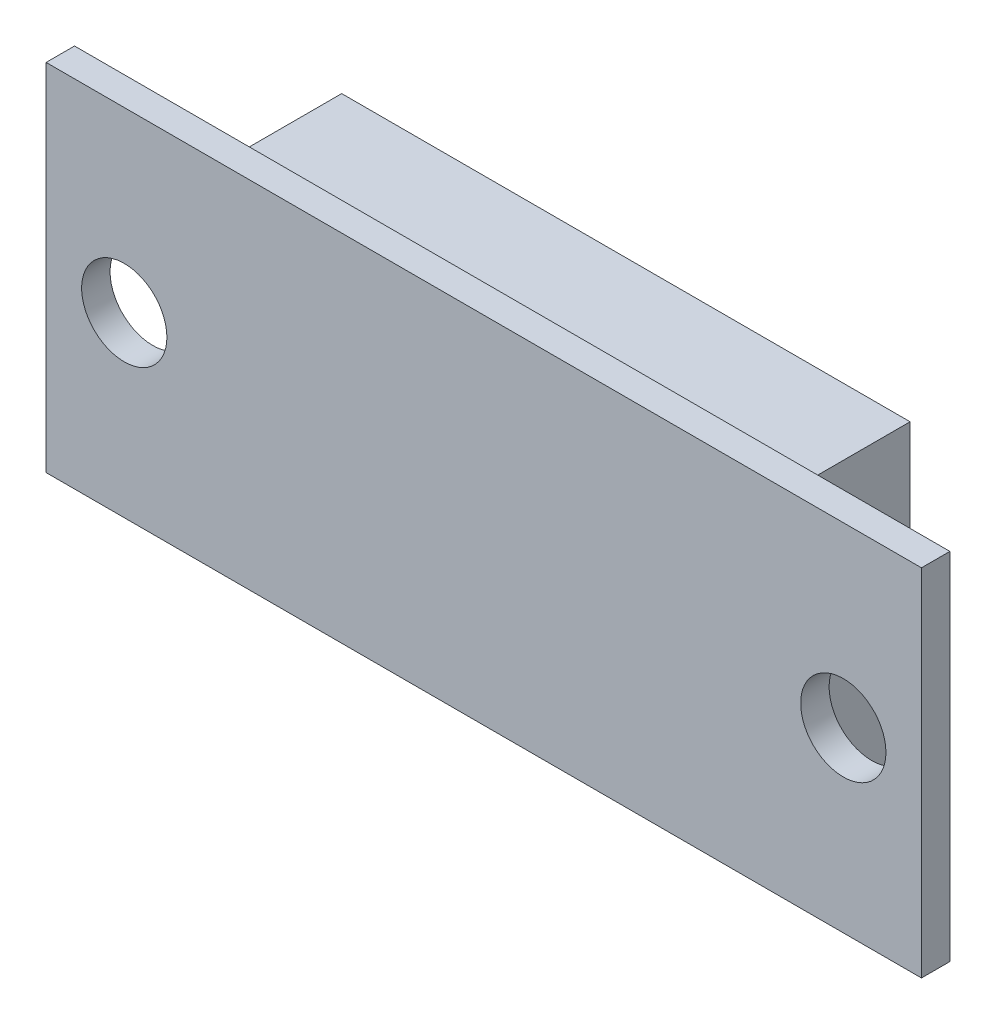
SolidWorks part; units mm, degrees
ref_plane "Front Plane" through (0, 0, 0) normal (0, 0, 1) x (1, 0, 0)
ref_plane "Top Plane" through (0, 0, 0) normal (0, 1, 0) x (1, 0, 0)
ref_plane "Right Plane" through (0, 0, 0) normal (1, 0, 0) x (0, 0, -1)
sketch "Sketch1" plane through (0, 0, 0) normal (0, 0, 1) x (1, 0, 0)
  line L1 (-10, 5.5) -> (10, 5.5)
  line L2 (-10, 5.5) -> (-10, -5.5)
  line L3 (-10, -5.5) -> (10, -5.5)
  line L4 (10, 5.5) -> (10, -5.5)
  line L5 (-10, 5.5) -> (10, -5.5) construction
  line L6 (-10, -5.5) -> (10, 5.5) construction
  point P0 (0, 0)
  point P1 (0, 0)
  dimension "D1" = 11
  dimension "D2" = 20
extrude "Boss-Extrude1" add sketch "Sketch1" along normal blind 4
sketch "Sketch2" plane through (0, 0, 4) normal (0, 0, 1) x (1, 0, 0)
  line L1 (-15.4, -6.25) -> (15.4, -6.25)
  line L2 (-15.4, -6.25) -> (-15.4, 6.25)
  line L3 (-15.4, 6.25) -> (15.4, 6.25)
  line L4 (15.4, -6.25) -> (15.4, 6.25)
  line L5 (-15.4, -6.25) -> (15.4, 6.25) construction
  line L6 (-15.4, 6.25) -> (15.4, -6.25) construction
  point P0 (0, 0)
  dimension "D1" = 30.8
  dimension "D2" = 12.5
extrude "Boss-Extrude2" add sketch "Sketch2" along normal blind 1
hole_wizard "Ø3.0 (3) Diameter Hole1" positions "Sketch4" profile "Sketch3" hole size "Ø3.0" standard "ISO" end condition up to next
sketch "Sketch4" plane through (0, 0, 5) normal (0, 0, 1) x (1, 0, 0)
  line L0 (-15.4, 6.25) -> (-15.4, -6.25) construction
  line L1 (15.4, -6.25) -> (15.4, 6.25) construction
  line L2 (-12.65, 0) -> (-12.65, -6.25) construction
  line L3 (-15.4, -6.25) -> (15.4, -6.25) construction
  line L5 (-12.65, 0) -> (-12.65, 6.25) construction
  line L6 (15.4, 6.25) -> (-15.4, 6.25) construction
  line L9 (12.65, 0) -> (12.65, -6.25) construction
  line L11 (12.65, 6.25) -> (12.65, 0) construction
  point P0 (-12.65, 0)
  point P1 (12.65, 0)
  dimension "D1" = 2.75
  dimension "D2" = 2.75
sketch "Sketch3" plane through (-12.65, 0, 5) normal (1, 0, 0) x (0, -1, 0)
  line L0 (0, 0) -> (0, 1)
  line L1 (0, 1) -> (1.5, 1)
  line L2 (1.5, 1) -> (1.5, 0)
  line L5 (1.5, 0) -> (0, 0)
  line L11 (0, -6.35) -> (0, 107.95) construction
  dimension "Thru Hole Dia." = 3
  dimension "Thru Hole Depth" = 1
